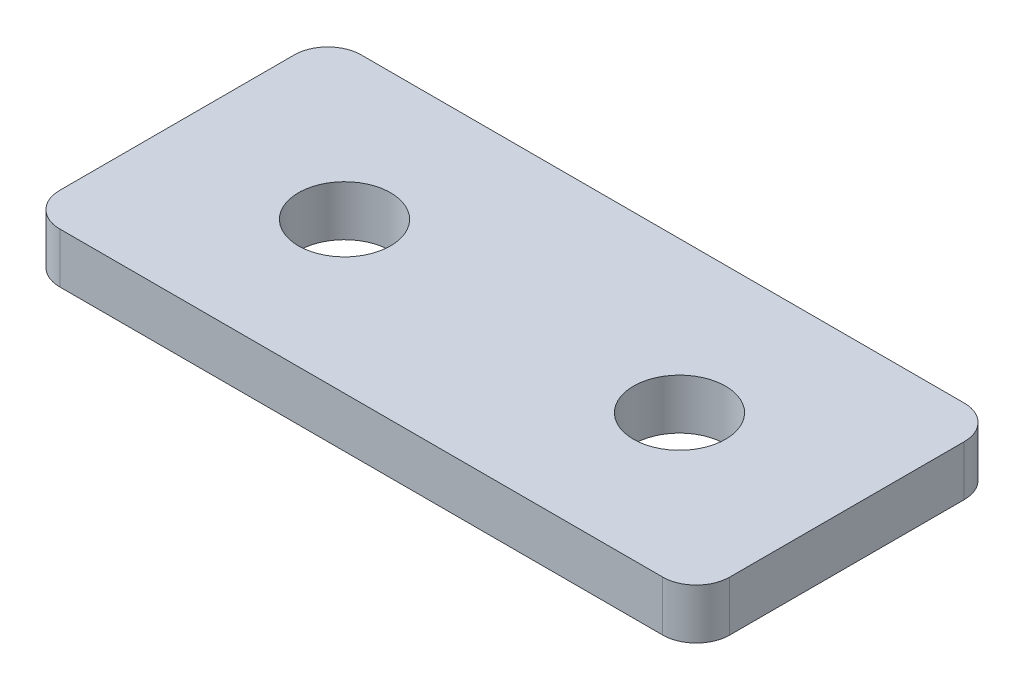
SolidWorks part; units mm, degrees
ref_plane "前视基准面" through (0, 0, 0) normal (0, 0, 1) x (1, 0, 0)
ref_plane "上视基准面" through (0, 0, 0) normal (0, 1, 0) x (1, 0, 0)
ref_plane "右视基准面" through (0, 0, 0) normal (1, 0, 0) x (0, 0, -1)
other "Configuration Table"
sketch "草图1" plane through (0, 0, 0) normal (0, 1, 0) x (1, 0, 0)
  line L0 (-1000, 0) -> (49000, 0) construction
  line L1 (-18, -9) -> (18, -9)
  line L2 (-20, -7) -> (-20, 7)
  line L3 (-18, 9) -> (18, 9)
  line L4 (20, -7) -> (20, 7)
  line L5 (-20, -9) -> (20, 9) construction
  line L6 (-20, 9) -> (20, -9) construction
  circle A0 centre (-10, 0) radius 2.75
  circle A1 centre (10, 0) radius 2.75
  arc A2 (18, 9) -> (20, 7) centre (18, 7) cw
  arc A3 (20, -7) -> (18, -9) centre (18, -7) cw
  arc A4 (-18, -9) -> (-20, -7) centre (-18, -7) cw
  arc A5 (-20, 7) -> (-18, 9) centre (-18, 7) cw
  point P0 (0, 0)
  dimension "D4" = 5.5
  dimension "D6" = 5.5
  dimension "D7" = 2
  dimension "D1" = 40
  dimension "D2" = 18
  dimension "D3" = 10
  dimension "D5" = 20
extrude "凸台-拉伸1" add sketch "草图1" along normal blind 3
